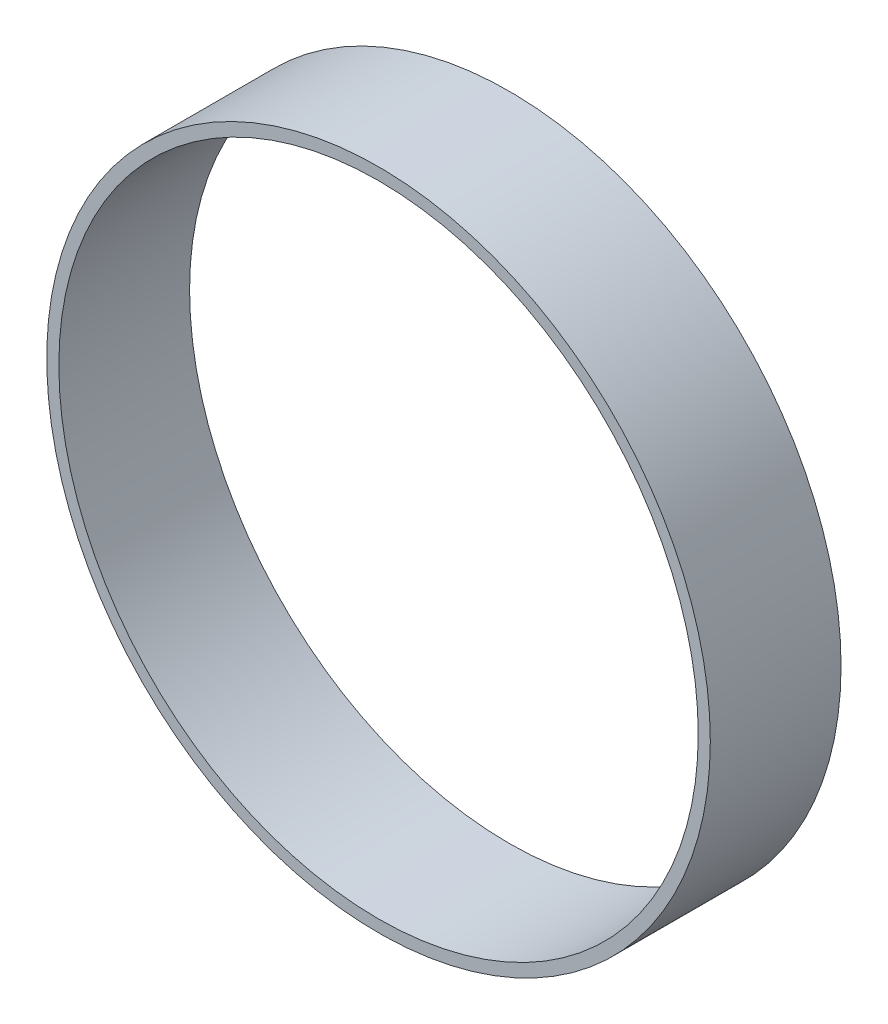
SolidWorks part; units mm, degrees
ref_plane "Front Plane" through (0, 0, 0) normal (0, 0, 1) x (1, 0, 0)
ref_plane "Top Plane" through (0, 0, 0) normal (0, 1, 0) x (1, 0, 0)
ref_plane "Right Plane" through (0, 0, 0) normal (1, 0, 0) x (0, 0, -1)
sketch "Sketch1" plane through (0, 0, 0) normal (0, 0, 1) x (1, 0, 0)
  circle A0 centre (0, 0) radius 12.96
  circle A2 centre (0, 0) radius 13.45
  dimension "D1" = 25.92
  dimension "D2" = 26.9
extrude "Boss-Extrude1" add sketch "Sketch1" along normal blind 5.3 contours A2 | A0
